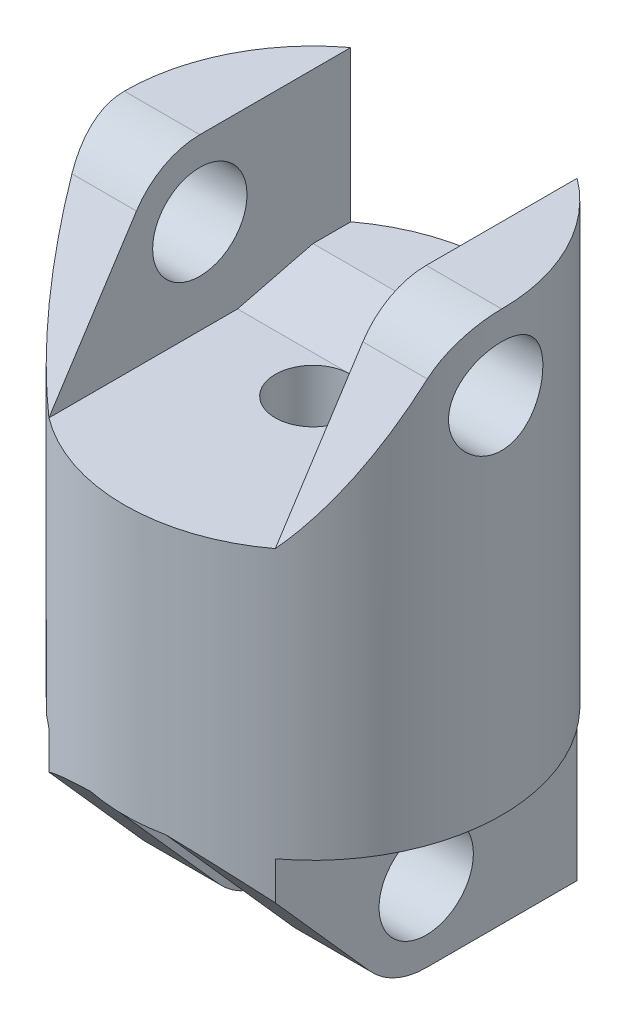
SolidWorks part; units mm, degrees
ref_plane "Front Plane" through (0, 0, 0) normal (0, 0, 1) x (1, 0, 0)
ref_plane "Top Plane" through (0, 0, 0) normal (0, 1, 0) x (1, 0, 0)
ref_plane "Right Plane" through (0, 0, 0) normal (1, 0, 0) x (0, 0, -1)
sketch "Sketch1" plane through (0, 0, 0) normal (0, 1, 0) x (1, 0, 0)
  circle A0 centre (0, 0) radius 12.7
  dimension "D1" = 25.4
extrude "Boss-Extrude1" add sketch "Sketch1" along normal blind 40.9448
sketch "Sketch2" plane through (0, 40.9448, 0) normal (0, 1, 0) x (1, 0, 0)
  line L0 (7.62, 10.16) -> (7.62, -10.16)
  line L1 (-7.62, 10.16) -> (-7.62, -10.16)
  arc A0 (-7.62, -10.16) -> (7.62, -10.16) centre (0, 0) ccw
  arc A1 (7.62, 10.16) -> (-7.62, 10.16) centre (0, 0) ccw
  dimension "D2" = 25.4
  dimension "D1" = 7.62
  dimension "D3" = 7.62
extrude "Cut-Extrude1" cut sketch "Sketch2" against normal blind 11.43
sketch "Sketch3" plane through (0, 0, 0) normal (0, -1, 0) x (1, 0, 0)
  line L0 (-2.54, 12.4434) -> (-2.54, -12.4434)
  line L1 (-7.62, 10.16) -> (-7.62, -10.16)
  line L2 (2.54, 12.4434) -> (2.54, -12.4434)
  line L3 (7.62, 10.16) -> (7.62, -10.16)
  arc A0 (-7.62, 10.16) -> (-7.62, -10.16) centre (0, 0) ccw
  arc A1 (-2.54, -12.4434) -> (2.54, -12.4434) centre (0, 0) ccw
  arc A2 (7.62, -10.16) -> (7.62, 10.16) centre (0, 0) ccw
  arc A3 (2.54, 12.4434) -> (-2.54, 12.4434) centre (0, 0) ccw
  dimension "D1" = 25.4
  dimension "D2" = 2.54
  dimension "D3" = 5.08
  dimension "D4" = 2.54
  dimension "D5" = 5.08
extrude "Cut-Extrude2" cut sketch "Sketch3" against normal blind 11.43
sketch "Sketch4" plane through (-7.62, 0, 0) normal (1, 0, 0) x (0, 0, -1)
  line L0 (10.16, 40.9448) -> (-10.16, 40.9448) construction
  line L5 (10.16, 0) -> (-10.16, 0) construction
  line L6 (10.16, 40.9448) -> (-10.16, 40.9448) construction
  line L7 (0, 40.9448) -> (-10.16, 40.9448)
  line L8 (-10.16, 40.9448) -> (-10.16, 29.5148)
  line L9 (-10.16, 29.5148) -> (-4.2649, 38.6247)
  line L10 (0, 0) -> (-12.4434, 0)
  line L11 (-12.4434, 0) -> (-10.16, 0) construction
  line L12 (-12.4434, 11.43) -> (-12.4434, 0) construction
  line L13 (-3.7964, 1.7046) -> (-12.4434, 11.43)
  line L14 (-12.4434, 11.43) -> (-12.4434, 0)
  circle A0 centre (0, 35.8648) radius 3.175
  circle A2 centre (0, 5.08) radius 3.175
  arc A4 (0, 40.9448) -> (-4.2649, 38.6247) centre (0, 35.8648) ccw
  arc A5 (0, 0) -> (-3.7964, 1.7046) centre (0, 5.08) cw
  dimension "D1" = 6.35
  dimension "D3" = 6.35
  dimension "D2" = 5.08
  dimension "D4" = 5.08
  dimension "D5" = 0
extrude "Cut-Extrude3" cut sketch "Sketch4" against normal through all both and the other way through all
sketch "Sketch5" plane through (0, 29.5148, 0) normal (0, 1, 0) x (1, 0, 0)
  circle A0 centre (0, 0) radius 2.54
  dimension "D1" = 5.08
extrude "Cut-Extrude4" cut sketch "Sketch5" against normal through all
sketch "Sketch6" plane through (-7.62, 0, 0) normal (1, 0, 0) x (0, 0, -1)
  line L0 (2.54, 29.5148) -> (10.16, 29.5148)
  line L1 (10.16, 29.5148) -> (-10.16, 29.5148) construction
  line L2 (10.16, 29.5148) -> (10.16, 30.7848)
  line L3 (10.16, 29.5148) -> (10.16, 40.9448) construction
  line L4 (10.16, 30.7848) -> (7.62, 30.7848)
  line L5 (7.62, 30.7848) -> (2.54, 29.5148)
  point P5 (0, 29.5148)
  dimension "D1" = 2.54
  dimension "D2" = 1.27
  dimension "D3" = 2.54
extrude "Boss-Extrude2" add sketch "Sketch6" along normal up to surface (15.24 mm away) up to face at (7.62, 35.8648, -3.175)
sketch "Sketch7" plane through (0, 29.5148, 0) normal (0, 1, 0) x (1, 0, 0)
  line L0 (-7.62, 10.16) -> (7.62, 10.16)
  arc A0 (7.62, 10.16) -> (-7.62, 10.16) centre (0, 0) ccw
  arc M1 (7.62, 10.16) -> (-7.62, 10.16) centre (0, 0) ccw
  line M2 (-7.62, 10.16) -> (7.62, 10.16)
extrude "Boss-Extrude3" add sketch "Sketch7" along normal up to surface (1.27 mm away) contours M2 M1 up to face at (0, 30.7848, -8.89)
